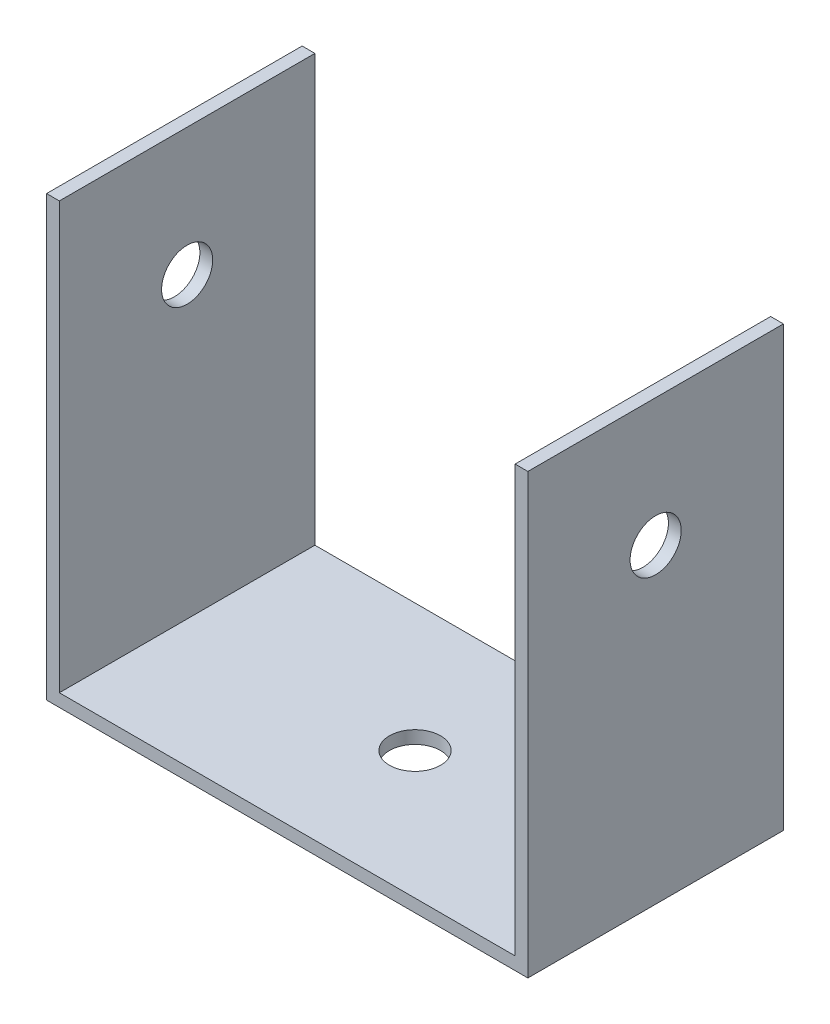
SolidWorks part; units mm, degrees
ref_plane "Front Plane" through (0, 0, 0) normal (0, 0, 1) x (1, 0, 0)
ref_plane "Top Plane" through (0, 0, 0) normal (0, 1, 0) x (1, 0, 0)
ref_plane "Right Plane" through (0, 0, 0) normal (1, 0, 0) x (0, 0, -1)
sketch "Sketch2" plane through (0, 0, 0) normal (0, 0, 1) x (1, 0, 0)
  line L0 (26.75, 0) -> (-26.75, 0)
  line L1 (-26.75, 0) -> (-26.75, 50)
  line L2 (-26.75, 50) -> (-28.25, 50)
  line L3 (-28.25, 50) -> (-28.25, -1.5)
  line L4 (-28.25, -1.5) -> (28.25, -1.5)
  line L5 (0, -1.5) -> (0, 29.0357) construction
  line L6 (26.75, 50) -> (28.25, 50)
  line L7 (28.25, 50) -> (28.25, -1.5)
  line L8 (26.75, 0) -> (26.75, 50)
  point P10 (0, 0)
  dimension "D1" = 1.5
  dimension "D2" = 1.5
  dimension "D3" = 50
  dimension "D4" = 55
extrude "Boss-Extrude1" add sketch "Sketch2" along normal blind 30
sketch "Sketch3" plane through (-28.25, 0, 0) normal (-1, 0, 0) x (0, 0, 1)
  line L0 (15, 50) -> (15, -1.5) construction
  line L1 (30, 50) -> (0, 50) construction
  line L2 (30, -1.5) -> (0, -1.5) construction
  circle A0 centre (15, 35) radius 3
  dimension "D2" = 6
  dimension "D1" = 15
extrude "Cut-Extrude1" cut sketch "Sketch3" against normal blind 60
sketch "Sketch4" plane through (0, 0, 0) normal (0, 1, 0) x (1, 0, 0)
  line L0 (0, 0) -> (0, -30) construction
  line L1 (26.75, -30) -> (-26.75, -30) construction
  circle A0 centre (0, -15) radius 3
  dimension "D1" = 6
extrude "Cut-Extrude2" cut sketch "Sketch4" against normal up to next
